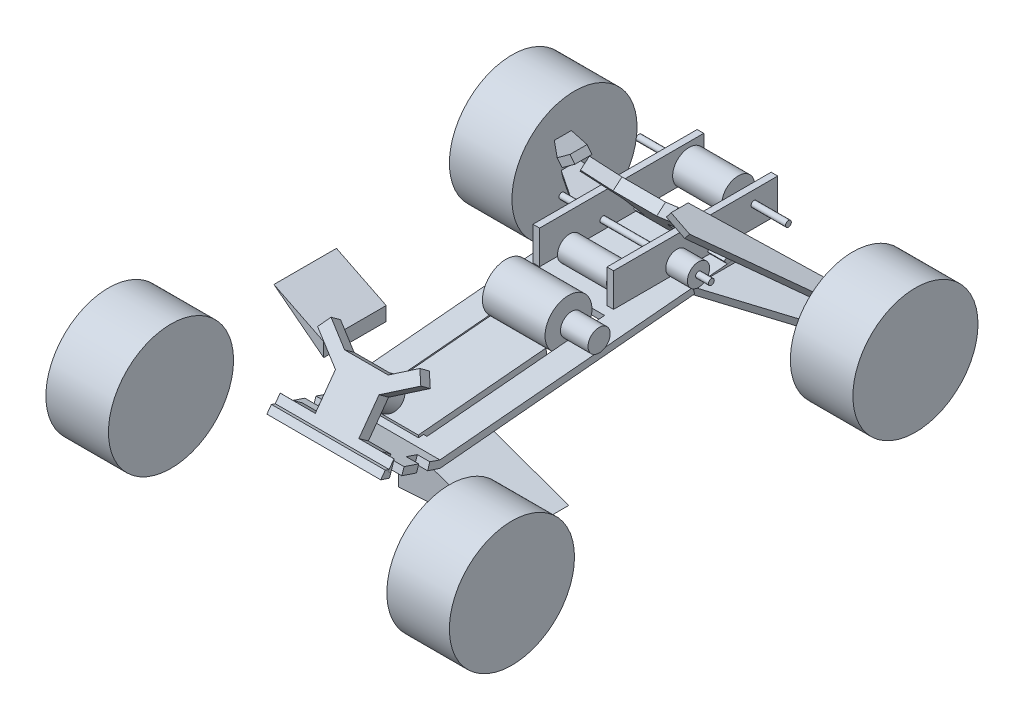
SolidWorks part; units mm, degrees
ref_plane "Front Plane" through (0, 0, 0) normal (0, 0, 1) x (1, 0, 0)
ref_plane "Top Plane" through (0, 0, 0) normal (0, 1, 0) x (1, 0, 0)
ref_plane "Right Plane" through (0, 0, 0) normal (1, 0, 0) x (0, 0, -1)
sketch "Sketch9" plane through (0, 0, 0) normal (0, 0, 1) x (1, 0, 0)
  line L0 (0, -70.122) -> (0, -33.481)
  line L1 (122.8379, -27.0671) -> (46.228, 0.3636) construction
  line L2 (0, -33.481) -> (87.5274, -64.8208)
  line L3 (87.5274, -64.8208) -> (0, -70.122)
  line L4 (122.8379, -16.0767) -> (41.2827, 47.0745) construction
  line L5 (-101.0903, 21.6646) -> (-60.6863, -9.6217)
  line L6 (-60.6863, -9.6217) -> (-60.6863, 1.6568)
  line L7 (-60.6863, 1.6568) -> (-101.0903, 21.6646)
extrude "Extrude8" add sketch "Sketch9" along normal blind 50.8 separate body
sketch "Sketch10" plane through (-10.6258, -29.6764, 0) normal (0.3371, 0.9415, 0) x (0.9415, -0.3371, 0)
  line L0 (44.6063, 142.204) -> (119.421, 197.3691)
  line L2 (119.421, 197.3691) -> (119.421, 210.7698)
  line L3 (119.421, 210.7698) -> (43.3997, 181.7875)
  line L5 (43.3997, 181.7875) -> (44.6063, 142.204)
extrude "Extrude9" add sketch "Sketch10" along normal blind 6.35 from offset 38.1 separate body
sketch "Sketch11" plane through (-27.4055, -35.3923, 0) normal (-0.6122, -0.7907, 0) x (0.7907, -0.6122, 0)
  line L0 (0, -143.4631) -> (96.5075, -206.1932)
  line L1 (96.5075, -206.1932) -> (96.5075, -193.0038)
  line L2 (96.5075, -193.0038) -> (16.0843, -131.8822)
  line L3 (16.0843, -131.8822) -> (0, -129.6303)
  line L4 (0, -129.6303) -> (0, -143.4631)
extrude "Extrude10" add sketch "Sketch11" along normal blind 6.35 from offset 111.76 separate body
sketch "Sketch1" plane through (0, 0, 0) normal (1, 0, 0) x (0, 0, -1)
  circle A0 centre (-122.4249, -27.0671) radius 50.8
  circle A1 centre (205.2351, -27.0671) radius 50.8
  dimension "D1" = 101.6
  dimension "D2" = 327.66
  dimension "D3" = 122.4249
extrude "Extrude1" add sketch "Sketch1" along normal blind 50.8 from offset 113.03
sketch "Sketch2" plane through (0, 0, 0) normal (1, 0, 0) x (0, 0, -1)
  line L0 (-111.3576, -11.8267) -> (-63.3175, -27.7789)
  line L1 (-63.3175, -27.7789) -> (185.9565, -4.5137)
  line L2 (-63.3175, -21.8002) -> (181.7875, 0.3636)
  line L3 (-107.7117, -6.8061) -> (-63.3175, -21.8002)
  line L5 (185.9565, -4.5137) -> (181.7875, 0.3636)
  line L6 (-111.3576, -11.8267) -> (-107.7117, -6.8061)
extrude "Extrude3" add sketch "Sketch2" along normal mid plane 92.456 separate body
mirror "Mirror1" about plane through (0, 0, 0) normal (1, 0, 0) of bodies 101 102 115
sketch "Sketch4" plane through (0, 32.8468, 78.9166) normal (0, 0.5876, 0.8092) x (1, 0, 0)
  line L0 (-46.228, -49.6075) -> (-46.228, -41.2548)
  line L1 (-46.228, -41.2548) -> (-17.7044, -41.2548)
  line L2 (-17.7044, -41.2548) -> (-17.7044, -13.3455)
  line L3 (-17.7044, -13.3455) -> (-41.908, 3.1578)
  line L4 (-41.908, 3.1578) -> (-36.0489, 11.7508)
  line L5 (-36.0489, 11.7508) -> (-17.7044, -0.7574)
  line L6 (-17.7044, -0.7574) -> (17.7044, -0.7574)
  line L7 (-46.228, -49.6075) -> (46.228, -49.6075)
  line L9 (0, 7.2361) -> (0, -54.4877) construction
  line L10 (36.0489, 11.7508) -> (17.7044, -0.7574)
  line L11 (41.908, 3.1578) -> (36.0489, 11.7508)
  line L12 (17.7044, -13.3455) -> (41.908, 3.1578)
  line L13 (17.7044, -41.2548) -> (17.7044, -13.3455)
  line L14 (46.228, -41.2548) -> (17.7044, -41.2548)
  line L15 (46.228, -49.6075) -> (46.228, -41.2548)
  point P11 (0, -49.6075)
  point P15 (0, -0.7574)
extrude "Extrude4" add sketch "Sketch4" along normal blind 9.525 from offset 12.7 separate body
sketch "Sketch5" plane through (0, 3.8672, -178.7926) normal (0, 0.6498, -0.7601) x (-1, 0, 0)
  line L0 (-46.228, -2.1731) -> (-46.228, 6.1797)
  line L1 (-46.228, 6.1797) -> (-17.7044, 6.1797)
  line L2 (-17.7044, 6.1797) -> (-17.7044, 34.089)
  line L3 (-17.7044, 34.089) -> (-41.908, 50.5922)
  line L4 (-41.908, 50.5922) -> (-36.0489, 59.1852)
  line L5 (-36.0489, 59.1852) -> (-17.7044, 46.677)
  line L6 (-17.7044, 46.677) -> (17.7044, 46.677)
  line L7 (-46.228, -2.1731) -> (46.228, -2.1731)
  line L8 (0, 54.6705) -> (0, -7.0533) construction
  line L9 (36.0489, 59.1852) -> (17.7044, 46.677)
  line L10 (41.908, 50.5922) -> (36.0489, 59.1852)
  line L11 (17.7044, 34.089) -> (41.908, 50.5922)
  line L12 (17.7044, 6.1797) -> (17.7044, 34.089)
  line L13 (46.228, 6.1797) -> (17.7044, 6.1797)
  line L14 (46.228, -2.1731) -> (46.228, 6.1797)
  point P10 (0, -2.1731)
  point P13 (0, 46.677)
extrude "Extrude5" add sketch "Sketch5" against normal blind 9.525 separate body
sketch "Sketch7" plane through (0, -15.9443, -1.4418) normal (0, 0.9959, 0.0901) x (1, 0, 0)
  line L0 (0, 17.7319) -> (0, 90.1219) construction
  line L1 (0, 17.7319) -> (25.4, 17.7319) construction
  line L2 (-25.4, 90.1219) -> (25.4, 90.1219)
  line L3 (25.4, 90.1219) -> (25.4, -54.6581)
  line L4 (-25.4, -54.6581) -> (25.4, -54.6581)
  line L5 (-25.4, 90.1219) -> (-25.4, -54.6581)
  point P8 (0, -54.6581)
  dimension "D1" = 144.78
  dimension "D2" = 90.1219
  dimension "D3" = 50.8
extrude "Extrude6" cut sketch "Sketch7" against normal blind 32.131
sketch "Sketch8" plane through (0, 0, 0) normal (1, 0, 0) x (0, 0, -1)
  circle A0 centre (61.903, 1.8037) radius 19.05
  dimension "D1" = 38.1
extrude "Extrude7" add sketch "Sketch8" along normal mid plane 50.8 separate body
sketch "Sketch13" plane through (0, 0, 0) normal (1, 0, 0) x (0, 0, -1)
  line L0 (-63.3175, -21.8002) -> (53.6327, -11.2249) construction
  line L1 (181.7875, 0.3636) -> (-63.3175, -21.8002) construction
  line L2 (-57.2133, -19.1913) -> (46.5035, -9.8127)
  line L3 (46.5035, -9.8127) -> (47.6472, -22.4611)
  line L4 (47.6472, -22.4611) -> (-56.0696, -31.8397)
  line L5 (-56.0696, -31.8397) -> (-57.2133, -19.1913)
  dimension "D1" = 12.7
  dimension "D2" = 104.14
extrude "Extrude11" add sketch "Sketch13" along normal mid plane 45.212 separate body
sketch "Sketch15" plane through (0, 0, 0) normal (1, 0, 0) x (0, 0, -1)
  line L0 (205.2351, -27.0671) -> (205.2351, 85.0215) construction
  circle A0 centre (108.1506, 8.4658) radius 9.8449
  circle A1 centre (205.2351, 17.1887) radius 13.3986
extrude "Extrude13" add sketch "Sketch15" along normal mid plane 39.878 separate body
sketch "Sketch14" plane through (25.4, 0, 0) normal (1, 0, 0) x (0, 0, -1)
  circle A0 centre (61.903, 1.8037) radius 9.0172
  circle A1 centre (142.6238, 7.5847) radius 9.0172
extrude "Extrude12" add sketch "Sketch14" along normal blind 22.352 from offset 2.54 separate body
sketch "Sketch16" plane through (0, 0, 0) normal (0, 1, 0) x (1, 0, 0)
  line L0 (32.7156, 91.2277) -> (32.7156, 224.5368)
  line L1 (32.7156, 224.5368) -> (27.3493, 224.5368)
  line L2 (27.3493, 224.5368) -> (27.3493, 91.1975)
  line L3 (27.3493, 91.1975) -> (32.7156, 91.2277)
  line L4 (0, 308.5948) -> (0, 45.1985) construction
  line L5 (-27.3493, 91.1975) -> (-32.7156, 91.2277)
  line L6 (-27.3493, 224.5368) -> (-27.3493, 91.1975)
  line L7 (-32.7156, 224.5368) -> (-27.3493, 224.5368)
  line L8 (-32.7156, 91.2277) -> (-32.7156, 224.5368)
extrude "Extrude14" add sketch "Sketch16" along normal blind 27.178 separate body
sketch "Sketch17" plane through (0, 0, 0) normal (1, 0, 0) x (0, 0, -1)
  circle A0 centre (142.6238, 7.5847) radius 2.3663
  circle A1 centre (205.2351, 17.1887) radius 2.3663
extrude "Extrude15" add sketch "Sketch17" along normal mid plane 121.412 separate body
sketch "Sketch19" plane through (0, 41.3997, 57.0103) normal (0, -0.5876, -0.8092) x (-1, 0, 0)
  circle A0 centre (0, -35.1102) radius 11.8806
extrude "Extrude16" add sketch "Sketch19" along normal blind 22.86 separate body
sketch "Sketch20" plane through (0, -43.9571, 14.5964) normal (0, -0.949, 0.3151) x (1, 0, 0)
  line L0 (54.6923, 94.5188) -> (36.0891, 94.5188)
  line L1 (36.0891, 94.5188) -> (36.0891, 83.9382)
  line L2 (36.0891, 83.9382) -> (48.8788, 83.9382)
  line L3 (48.8788, 83.9382) -> (48.8788, 71.3811)
  line L4 (48.8788, 71.3811) -> (36.0891, 71.3811)
  line L5 (36.0891, 71.3811) -> (36.0891, 61.847)
  line L6 (36.0891, 61.847) -> (53.6458, 61.847)
  line L7 (53.6458, 61.847) -> (54.6923, 94.5188)
  line L8 (0, 135.1129) -> (0, -20.6529) construction
  line L9 (-53.6458, 61.847) -> (-54.6923, 94.5188)
  line L10 (-36.0891, 61.847) -> (-53.6458, 61.847)
  line L11 (-36.0891, 71.3811) -> (-36.0891, 61.847)
  line L12 (-48.8788, 71.3811) -> (-36.0891, 71.3811)
  line L13 (-48.8788, 83.9382) -> (-48.8788, 71.3811)
  line L14 (-36.0891, 83.9382) -> (-48.8788, 83.9382)
  line L15 (-36.0891, 94.5188) -> (-36.0891, 83.9382)
  line L16 (-54.6923, 94.5188) -> (-36.0891, 94.5188)
extrude "Extrude17" cut sketch "Sketch20" against normal blind 22.86
